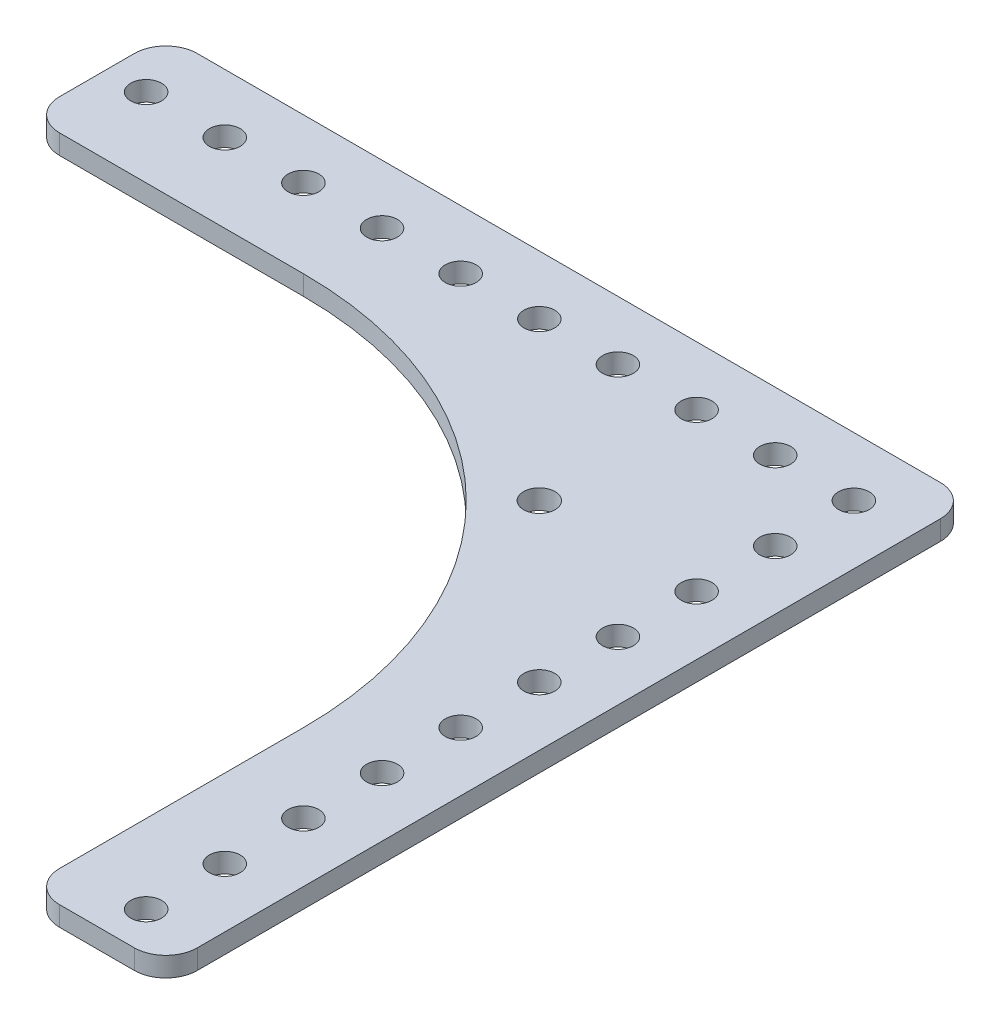
SolidWorks part; units mm, degrees
ref_plane "Front Plane" through (0, 0, 0) normal (0, 0, 1) x (1, 0, 0)
ref_plane "Top Plane" through (0, 0, 0) normal (0, 1, 0) x (1, 0, 0)
ref_plane "Right Plane" through (0, 0, 0) normal (1, 0, 0) x (0, 0, -1)
sketch "Sketch1" plane through (0, 0, 0) normal (0, 1, 0) x (1, 0, 0)
  line B0 (0, 63.5) -> (-33.02, 63.5)
  line B1 (-38.1, 68.58) -> (-38.1, 77.47)
  line B2 (-33.02, 82.55) -> (77.47, 82.55)
  line B3 (82.55, 77.47) -> (82.55, -33.02)
  line B4 (77.47, -38.1) -> (68.58, -38.1)
  line B5 (63.5, -33.02) -> (63.5, 0)
  arc B6 (0, 63.5) -> (63.5, 0) centre (0, 0) cw
  arc B7 (68.58, -38.1) -> (63.5, -33.02) centre (68.58, -33.02) cw
  arc B8 (82.55, -33.02) -> (77.47, -38.1) centre (77.47, -33.02) cw
  arc B9 (77.47, 82.55) -> (82.55, 77.47) centre (77.47, 77.47) cw
  arc B10 (-38.1, 77.47) -> (-33.02, 82.55) centre (-33.02, 77.47) cw
  arc B11 (-33.02, 63.5) -> (-38.1, 68.58) centre (-33.02, 68.58) cw
  circle B12 centre (-28.575, 73.025) radius 2.4892
  circle B13 centre (-15.875, 73.025) radius 2.4892
  circle B14 centre (-3.175, 73.025) radius 2.4892
  circle B15 centre (9.525, 73.025) radius 2.4892
  circle B16 centre (22.225, 73.025) radius 2.4892
  circle B17 centre (34.925, 73.025) radius 2.4892
  circle B18 centre (47.625, 73.025) radius 2.4892
  circle B19 centre (60.325, 73.025) radius 2.4892
  circle B20 centre (73.025, 73.025) radius 2.4892
  circle B21 centre (73.025, 60.325) radius 2.4892
  circle B22 centre (73.025, 47.625) radius 2.4892
  circle B23 centre (73.025, 34.925) radius 2.4892
  circle B24 centre (73.025, 22.225) radius 2.4892
  circle B25 centre (73.025, 9.525) radius 2.4892
  circle B26 centre (73.025, -3.175) radius 2.4892
  circle B27 centre (73.025, -15.875) radius 2.4892
  circle B28 centre (73.025, -28.575) radius 2.4892
  circle B29 centre (50.8, 50.8) radius 2.54
sketch_block_instance "Block-Bumper_Gussest-1"
sketch_block "Block-Bumper_Gussest" parameters "D1"=63.5, "D2"=5.08, "D3"=4.9784, "D8"=5.08, "D4"=9.525, "D5"=9.525, "D6"=12.7, "D7"=9.525, "D9"=31.75, "D10"=31.75
extrude "Boss-Extrude1" add sketch "Sketch1" along normal blind 3.175
sketch "Sketch3" plane through (0, 3.175, 0) normal (0, 1, 0) x (1, 0, 0)
  line L0 (-38.1, 66.675) -> (66.675, 66.675)
  line L1 (66.675, 66.675) -> (66.675, -38.1)
  line L2 (68.58, -38.1) -> (77.47, -38.1) construction
  line L4 (-39.37, 85.725) -> (80.645, 85.725)
  line L5 (85.725, 80.645) -> (85.725, -39.37)
  line L6 (63.5, 0) -> (63.5, -33.02)
  line L7 (68.58, -38.1) -> (77.47, -38.1)
  line L8 (82.55, -33.02) -> (82.55, 77.47)
  line L9 (77.47, 82.55) -> (-33.02, 82.55)
  line L10 (-38.1, 77.47) -> (-38.1, 68.58)
  line L11 (-33.02, 63.5) -> (0, 63.5)
  line L12 (63.5, 0) -> (63.5, -33.02)
  line L17 (-33.02, 63.5) -> (0, 63.5)
  line L19 (-38.1, 77.47) -> (-38.1, 68.58) construction
  line L20 (-33.02, 63.5) -> (-39.37, 63.5)
  line L23 (-44.45, 68.58) -> (-44.45, 80.645)
  line L26 (63.5, -33.02) -> (63.5, -39.37)
  line L27 (68.58, -44.45) -> (80.645, -44.45)
  circle A0 centre (50.8, 50.8) radius 2.54 construction
  circle A1 centre (50.8, 50.8) radius 2.54
  circle A2 centre (-28.575, 73.025) radius 2.4892 construction
  circle A3 centre (-15.875, 73.025) radius 2.4892 construction
  arc A5 (80.645, 85.725) -> (85.725, 80.645) centre (80.645, 80.645) cw
  arc A6 (63.5, 0) -> (0, 63.5) centre (0, 0) ccw
  arc A7 (63.5, -33.02) -> (68.58, -38.1) centre (68.58, -33.02) ccw
  arc A8 (77.47, -38.1) -> (82.55, -33.02) centre (77.47, -33.02) ccw
  arc A9 (82.55, 77.47) -> (77.47, 82.55) centre (77.47, 77.47) ccw
  arc A10 (-33.02, 82.55) -> (-38.1, 77.47) centre (-33.02, 77.47) ccw
  arc A11 (-38.1, 68.58) -> (-33.02, 63.5) centre (-33.02, 68.58) ccw
  arc A12 (63.5, 0) -> (0, 63.5) centre (0, 0) ccw
  circle A19 centre (-3.175, 73.025) radius 2.4892 construction
  circle A20 centre (9.525, 73.025) radius 2.4892 construction
  circle A21 centre (73.025, -28.575) radius 2.4892 construction
  circle A22 centre (73.025, -15.875) radius 2.4892 construction
  circle A23 centre (73.025, -3.175) radius 2.4892 construction
  circle A24 centre (73.025, 9.525) radius 2.4892 construction
  circle A25 centre (73.025, 22.225) radius 2.4892 construction
  circle A26 centre (73.025, 34.925) radius 2.4892 construction
  circle A27 centre (73.025, 47.625) radius 2.4892 construction
  circle A28 centre (73.025, 60.325) radius 2.4892 construction
  circle A29 centre (73.025, 73.025) radius 2.4892 construction
  circle A30 centre (60.325, 73.025) radius 2.4892 construction
  circle A31 centre (47.625, 73.025) radius 2.4892 construction
  circle A32 centre (34.925, 73.025) radius 2.4892 construction
  circle A33 centre (22.225, 73.025) radius 2.4892 construction
  circle A34 centre (73.025, -28.575) radius 2.4892
  circle A35 centre (73.025, -15.875) radius 2.4892
  circle A36 centre (73.025, -3.175) radius 2.4892
  circle A37 centre (73.025, 9.525) radius 2.4892
  circle A38 centre (73.025, 22.225) radius 2.4892
  circle A39 centre (73.025, 34.925) radius 2.4892
  circle A40 centre (73.025, 47.625) radius 2.4892
  circle A41 centre (73.025, 60.325) radius 2.4892
  circle A42 centre (73.025, 73.025) radius 2.4892
  circle A43 centre (60.325, 73.025) radius 2.4892
  circle A44 centre (47.625, 73.025) radius 2.4892
  circle A45 centre (34.925, 73.025) radius 2.4892
  circle A46 centre (22.225, 73.025) radius 2.4892
  circle A47 centre (9.525, 73.025) radius 2.4892
  circle A48 centre (-3.175, 73.025) radius 2.4892
  circle A49 centre (-15.875, 73.025) radius 2.4892
  circle A50 centre (-28.575, 73.025) radius 2.4892
  arc A55 (63.5, -39.37) -> (68.58, -44.45) centre (68.58, -39.37) ccw
  arc A56 (-39.37, 63.5) -> (-44.45, 68.58) centre (-39.37, 68.58) cw
  arc A57 (-39.37, 85.725) -> (-44.45, 80.645) centre (-39.37, 80.645) ccw
  arc A58 (80.645, -44.45) -> (85.725, -39.37) centre (80.645, -39.37) ccw
  dimension "D6" = 5.08
  dimension "D9" = 5.08
  dimension "D10" = 5.08
  dimension "D2" = 3.175
  dimension "D3" = 3.175
  dimension "D4" = 19.05
  dimension "D5" = 6.35
  dimension "D7" = 6.35
  dimension "D8" = 19.05
  dimension "D1" = 0
extrude "Boss-Extrude2" add sketch "Sketch3" against normal up to surface (3.175 mm away) up to face at (73.025, 0, 31.0642)
sketch "Sketch4" plane through (0, 3.175, 0) normal (0, 1, 0) x (1, 0, 0)
  line L0 (-44.45, 66.675) -> (66.675, 66.675)
  line L2 (66.675, 66.675) -> (66.675, -44.45)
  line L4 (-39.37, 63.5) -> (0, 63.5) construction
  line L5 (63.5, 0) -> (63.5, -39.37) construction
  line L6 (-44.45, 68.58) -> (-44.45, 80.645) construction
  line L7 (68.58, -44.45) -> (80.645, -44.45) construction
  line L8 (85.725, 80.645) -> (85.725, -39.37) construction
  line L9 (76.2, 76.2) -> (63.5, 76.2) construction
  line L10 (76.2, 76.2) -> (76.2, 63.5) construction
  circle A0 centre (76.2, 76.2) radius 2.4892
  circle A1 centre (63.5, 76.2) radius 2.4892
  circle A2 centre (50.8, 76.2) radius 2.4892
  circle A3 centre (38.1, 76.2) radius 2.4892
  circle A4 centre (25.4, 76.2) radius 2.4892
  circle A5 centre (12.7, 76.2) radius 2.4892
  circle A6 centre (0, 76.2) radius 2.4892
  circle A7 centre (-12.7, 76.2) radius 2.4892
  circle A8 centre (-25.4, 76.2) radius 2.4892
  circle A10 centre (76.2, 63.5) radius 2.4892
  circle A11 centre (76.2, 50.8) radius 2.4892
  circle A12 centre (76.2, 38.1) radius 2.4892
  circle A13 centre (76.2, 25.4) radius 2.4892
  circle A14 centre (76.2, 12.7) radius 2.4892
  circle A15 centre (76.2, 0) radius 2.4892
  circle A16 centre (76.2, -12.7) radius 2.4892
  circle A17 centre (76.2, -25.4) radius 2.4892
  circle A18 centre (-38.1, 76.2) radius 2.4892
  circle A19 centre (76.2, -38.1) radius 2.4892
  dimension "D3" = 9.525
  dimension "D5" = 4.9784
  dimension "D1" = 3.175
  dimension "D2" = 3.175
  dimension "D4" = 9.525
  dimension "D7" = 12.7
  dimension "D9" = 12.7
  dimension "D6" = 10
  dimension "D8" = 10
extrude "Cut-Extrude1" cut sketch "Sketch4" against normal through all contours A1 | A0 | A10 | A11 | A12 | A2 | A3 | A4 | A17 | A16 | A15 | A14 | A13 | A5 | A6 | A7 | A18 | A8 | A19
